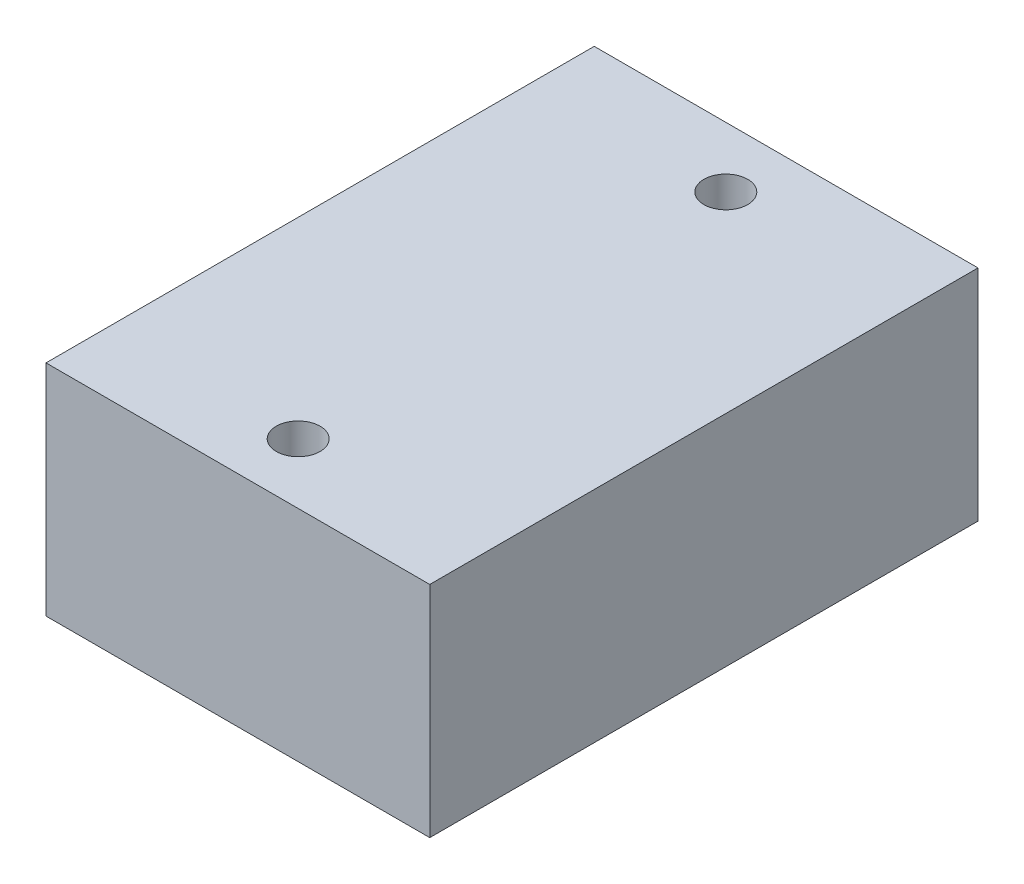
SolidWorks part; units mm, degrees
ref_plane "前视基准面" through (0, 0, 0) normal (0, 0, 1) x (1, 0, 0)
ref_plane "上视基准面" through (0, 0, 0) normal (0, 1, 0) x (1, 0, 0)
ref_plane "右视基准面" through (0, 0, 0) normal (1, 0, 0) x (0, 0, -1)
sketch "草图1" plane through (0, 0, 0) normal (0, 1, 0) x (1, 0, 0)
  line L0 (0, -19.5) -> (0, 19.5) construction
  line L1 (-17.5, 25) -> (17.5, 25)
  line L2 (-17.5, 25) -> (-17.5, -25)
  line L3 (-17.5, -25) -> (17.5, -25)
  line L4 (17.5, 25) -> (17.5, -25)
  line L5 (-17.5, 25) -> (17.5, -25) construction
  line L6 (-17.5, -25) -> (17.5, 25) construction
  circle A0 centre (0, 19.5) radius 2
  circle A1 centre (0, -19.5) radius 2
  point P0 (0, 0)
  point P9 (0, 0)
  dimension "D4" = 4
  dimension "D5" = 4
  dimension "D1" = 35
  dimension "D2" = 50
  dimension "D3" = 39
extrude "凸台-拉伸1" add sketch "草图1" along normal blind 20
